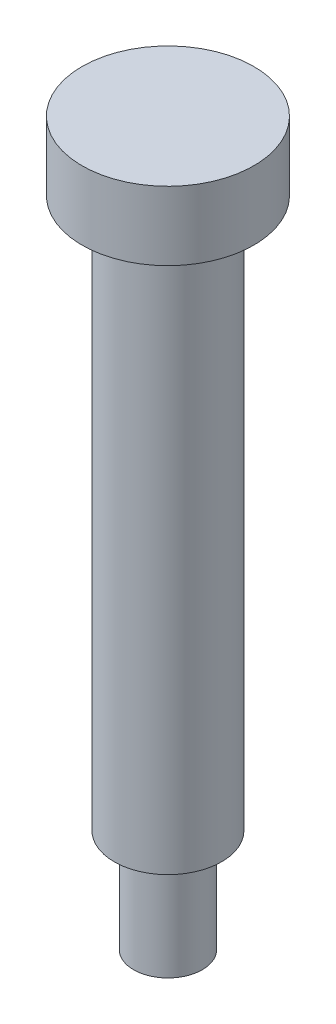
SolidWorks part; units mm, degrees
ref_plane "Front Plane" through (0, 0, 0) normal (0, 0, 1) x (1, 0, 0)
ref_plane "Top Plane" through (0, 0, 0) normal (0, 1, 0) x (1, 0, 0)
ref_plane "Right Plane" through (0, 0, 0) normal (1, 0, 0) x (0, 0, -1)
sketch "Sketch2" plane through (0, 0, 0) normal (0, 0, 1) x (1, 0, 0)
  line L0 (0, 0) -> (2, 0)
  line L1 (2, 0) -> (2, 6)
  line L2 (2, 6) -> (3.125, 6)
  line L3 (3.125, 6) -> (3.125, 38)
  line L4 (3.125, 38) -> (5, 38)
  line L5 (5, 38) -> (5, 42)
  line L6 (5, 42) -> (0, 42)
  line L7 (0, 42) -> (0, 0)
  dimension "D1" = 42
  dimension "D2" = 4
  dimension "D3" = 32
  dimension "D4" = 2
  dimension "D5" = 3.125
  dimension "D6" = 5
revolve "Revolve1" add sketch "Sketch2" angle 360 about L7
